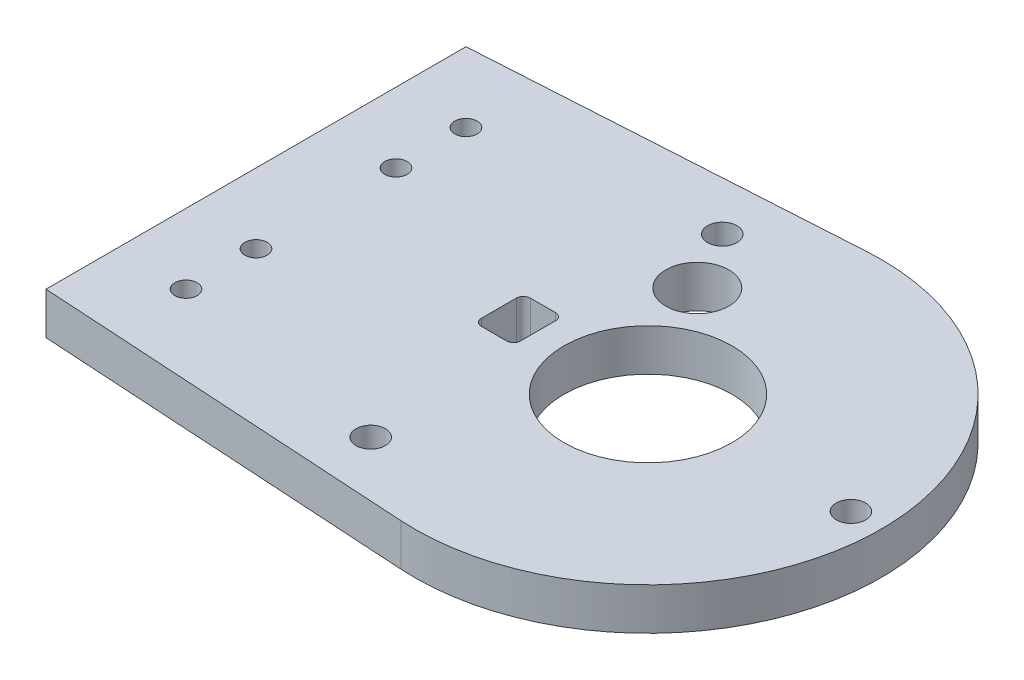
SolidWorks part; units mm, degrees
material "Thornel Mat VMA"
ref_plane "前视基准面" through (0, 0, 0) normal (0, 0, 1) x (1, 0, 0)
ref_plane "上视基准面" through (0, 0, 0) normal (0, 1, 0) x (1, 0, 0)
ref_plane "右视基准面" through (0, 0, 0) normal (1, 0, 0) x (0, 0, -1)
other "Configuration Table"
sketch "草图1" plane through (0, 0, 0) normal (0, 1, 0) x (1, 0, 0)
  line L2 (-56, -30) -> (-56, 30)
  line L5 (-64.1529, 0) -> (90.3429, 0) construction
  line L12 (-56, -30) -> (-2.0281, -33.2883)
  line L13 (-2.0281, 33.2883) -> (-56, 30)
  arc A1 (-2.0281, 33.2883) -> (-2.0281, -33.2883) centre (0, 0) cw
  point P0 (0, 0)
  dimension "D3" = 33.35
  dimension "D1" = 60
  dimension "D2" = 56
extrude "凸台-拉伸1" add sketch "草图1" along normal blind 6
sketch "草图4" plane through (0, 6, 0) normal (0, 1, 0) x (1, 0, 0)
  arc A0 (-2.0281, -33.2883) -> (-2.0281, 33.2883) centre (0, 0) ccw construction
  arc A1 (-2.0281, -33.2883) -> (-2.0281, 33.2883) centre (0, 0) ccw construction
  circle A2 centre (0, 0) radius 12
  dimension "D1" = 24
extrude "切除-拉伸2" cut sketch "草图4" against normal up to surface (6 mm away) up to face at (-20.1695, 0, 0)
sketch "草图5" plane through (0, 6, 0) normal (0, 1, 0) x (1, 0, 0)
  line L0 (-55.6212, 0) -> (47.7463, 0) construction
  line L1 (-56, 30) -> (-56, -30) construction
  line L2 (-56, 30) -> (-20.8319, 30) construction
  circle A0 centre (-46, 20) radius 1.6
  circle A1 centre (-46, 10) radius 1.6
  circle A2 centre (-46, -20) radius 1.6
  circle A3 centre (-46, -10) radius 1.6
  dimension "D1" = 3.2
  dimension "D3" = 10
  dimension "D4" = 3.2
  dimension "D5" = 10
  dimension "D2" = 10
extrude "切除-拉伸3" cut sketch "草图5" against normal up to surface (6 mm away) up to face at (0, 0, -12)
sketch "草图6" plane through (0, 6, 0) normal (0, 1, 0) x (1, 0, 0)
  line L0 (-55.9666, 0) -> (53.6195, 0) construction
  circle A0 centre (19.25, 0) radius 4.5 construction
  circle A1 centre (-9.625, -16.671) radius 4.5 construction
  circle A2 centre (-9.625, 16.671) radius 4.5
  circle A3 centre (29, 0) radius 2.1
  circle A4 centre (-14.5, -25.1147) radius 2.1
  circle A5 centre (-14.5, 25.1147) radius 2.1
  point P11 (0, 0)
  point P15 (0, 0)
  point P18 (0, 0)
  point P21 (0, 0)
  dimension "D2" = 9
  dimension "D4" = 4.2
  dimension "D1" = 19.25
  dimension "D5" = 29
  dimension "D3" = 3
  dimension "D6" = 3
extrude "切除-拉伸4" cut sketch "草图6" against normal up to surface (6 mm away) up to face at (-46, 0, -21.6)
sketch "草图7" plane through (0, 6, 0) normal (0, 1, 0) x (1, 0, 0)
  line L0 (-5.7339, 0) -> (-61.978, 0) construction
  line L2 (-15.7, -3.5) -> (-21.3, -3.5)
  line L3 (-15.7, -3.5) -> (-15.7, 3.5)
  line L4 (-15.7, 3.5) -> (-21.3, 3.5)
  line L5 (-21.3, -3.5) -> (-21.3, 3.5)
  line L6 (-15.7, -3.5) -> (-21.3, 3.5) construction
  line L7 (-15.7, 3.5) -> (-21.3, -3.5) construction
  point P3 (-18.5, 0)
  dimension "D1" = 18.5
  dimension "D2" = 5.6
  dimension "D3" = 7
extrude "切除-拉伸5" cut sketch "草图7" against normal up to surface (6 mm away) up to face at (-14.5, 0, -27.2147)
fillet "圆角2" radius 1 4 edges at (-15.7, 3, 3.5) (-21.3, 3, 3.5) (-21.3, 3, -3.5) (-15.7, 3, -3.5)
